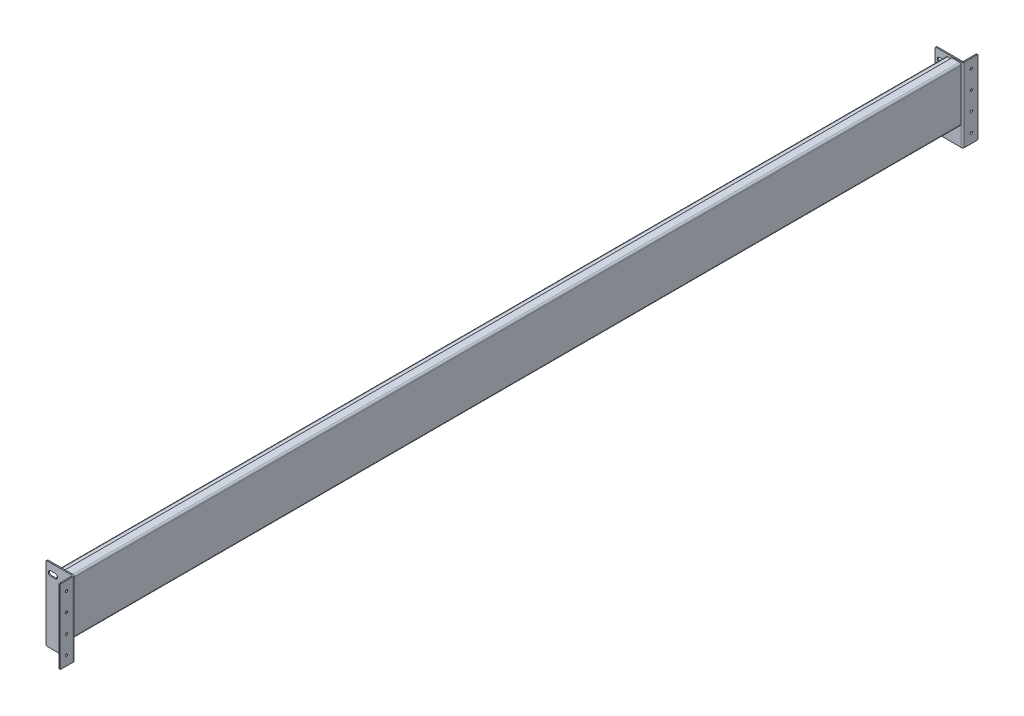
SolidWorks part; units mm, degrees
material "ASTM A36 Steel"
ref_plane "Front Plane" through (0, 0, 0) normal (0, 0, 1) x (1, 0, 0)
ref_plane "Top Plane" through (0, 0, 0) normal (0, 1, 0) x (1, 0, 0)
ref_plane "Right Plane" through (0, 0, 0) normal (1, 0, 0) x (0, 0, -1)
sketch "Sketch1" plane through (0, 0, 0) normal (0, 0, 1) x (1, 0, 0)
  line L0 (6.35, 71.4375) -> (26.9875, 71.4375)
  line L1 (-22.225, -74.6125) -> (26.9875, -74.6125)
  line L2 (28.575, -69.85) -> (28.575, 69.85)
  line L3 (6.35, 74.6125) -> (26.9875, 74.6125)
  line L4 (31.75, -69.85) -> (31.75, 69.85)
  line L5 (-31.75, -74.6125) -> (31.75, 74.6125) construction
  line L6 (-31.75, 74.6125) -> (31.75, -74.6125) construction
  line L7 (0, 0) -> (0, 50000) construction
  line L8 (0, 0) -> (50000, 0) construction
  line L9 (-22.225, -71.4375) -> (26.9875, -71.4375)
  line L10 (6.35, 74.6125) -> (6.35, 71.4375)
  line L11 (-22.225, -71.4375) -> (-22.225, -74.6125)
  arc A0 (26.9875, 74.6125) -> (31.75, 69.85) centre (26.9875, 69.85) cw
  arc A1 (31.75, -69.85) -> (26.9875, -74.6125) centre (26.9875, -69.85) cw
  arc A2 (26.9875, 71.4375) -> (28.575, 69.85) centre (26.9875, 69.85) cw
  arc A3 (28.575, -69.85) -> (26.9875, -71.4375) centre (26.9875, -69.85) cw
  point P0 (0, 0)
  dimension "D3" = 4.7625
  dimension "D1" = 149.225
  dimension "D2" = 63.5
  dimension "D4" = 74.6125
  dimension "D5" = 25.4
  dimension "D6" = 31.75
  dimension "D7" = 22.225
  dimension "D8" = 3.175
extrude "Boss-Extrude1" add sketch "Sketch1" along normal blind 1216.025 and the other way blind 1216.025
sketch "Sketch2" plane through (0, 0, 0) normal (0, 0, 1) x (1, 0, 0)
  line L0 (22.225, 71.4375) -> (-4.7625, 71.4375)
  line L1 (6.35, 71.4375) -> (26.9875, 71.4375) construction
  line L2 (-9.525, 66.675) -> (-9.525, 38.1)
  line L3 (-14.2875, 33.3375) -> (-26.9875, 33.3375)
  line L4 (-31.75, 28.575) -> (-31.75, -66.675)
  line L5 (-26.9875, -71.4375) -> (22.225, -71.4375)
  line L6 (26.9875, -71.4375) -> (-22.225, -71.4375) construction
  line L7 (31.75, -69.85) -> (31.75, 69.85) construction
  line L11 (26.9875, 74.6125) -> (6.35, 74.6125) construction
  line L12 (28.575, 69.85) -> (28.575, -69.85) construction
  line L13 (22.225, 68.2625) -> (-4.7625, 68.2625)
  line L14 (-6.35, 66.675) -> (-6.35, 38.1)
  line L15 (-14.2875, 30.1625) -> (-26.9875, 30.1625)
  line L16 (-28.575, 28.575) -> (-28.575, -66.675)
  line L17 (-26.9875, -68.2625) -> (22.225, -68.2625)
  line L18 (22.225, 68.2625) -> (22.225, 71.4375)
  line L19 (22.225, -68.2625) -> (22.225, -71.4375)
  arc A0 (-26.9875, -71.4375) -> (-31.75, -66.675) centre (-26.9875, -66.675) cw
  arc A1 (-4.7625, 71.4375) -> (-9.525, 66.675) centre (-4.7625, 66.675) ccw
  arc A2 (-9.525, 38.1) -> (-14.2875, 33.3375) centre (-14.2875, 38.1) cw
  arc A3 (-26.9875, 33.3375) -> (-31.75, 28.575) centre (-26.9875, 28.575) ccw
  arc A4 (-4.7625, 68.2625) -> (-6.35, 66.675) centre (-4.7625, 66.675) ccw
  arc A5 (-6.35, 38.1) -> (-14.2875, 30.1625) centre (-14.2875, 38.1) cw
  arc A6 (-26.9875, 30.1625) -> (-28.575, 28.575) centre (-26.9875, 28.575) ccw
  arc A7 (-26.9875, -68.2625) -> (-28.575, -66.675) centre (-26.9875, -66.675) cw
  point P21 (-31.75, -71.4375)
  point P28 (-31.75, 33.3375)
  dimension "D7" = 4.7625
  dimension "D1" = 63.5
  dimension "D2" = 22.225
  dimension "D3" = 41.275
  dimension "D4" = 104.775
  dimension "D5" = 6.35
  dimension "D6" = 6.35
  dimension "D8" = 3.175
extrude "Boss-Extrude2" add sketch "Sketch2" along normal up to surface and the other way up to surface separate body
sketch "Sketch4" plane through (0, -74.6125, 0) normal (0, -1, 0) x (1, 0, 0)
  line L0 (-22.225, 1216.025) -> (26.9875, 1216.025) construction
  line L1 (-39.6875, 1216.025) -> (31.75, 1216.025)
  line L2 (33.3375, 1220.7875) -> (33.3375, 1257.3)
  line L3 (-26.9875, 1216.025) -> (-31.75, 1216.025) construction
  line L4 (-26.9875, 1216.025) -> (-31.75, 1216.025) construction
  line L5 (-39.6875, 1219.2) -> (31.75, 1219.2)
  line L6 (33.3375, 1257.3) -> (36.5125, 1257.3)
  line L7 (-39.6875, 1219.2) -> (-39.6875, 1216.025)
  line L8 (36.5125, 1257.3) -> (36.5125, 1220.7875)
  line L10 (-39.6875, 1216.025) -> (39.0982, 1216.025) construction
  line L11 (36.5125, 1830.3646) -> (36.5125, 1866.9) construction
  line L12 (33.3375, 1828.0786) -> (33.3375, 1866.9) construction
  line L13 (-39.6875, 1219.2) -> (38.5604, 1219.2) construction
  arc A0 (36.5125, 1220.7875) -> (31.75, 1216.025) centre (31.75, 1220.7875) cw
  arc A1 (33.3375, 1220.7875) -> (31.75, 1219.2) centre (31.75, 1220.7875) cw
  arc A2 (36.5125, 1830.3646) -> (39.0982, 1216.025) centre (-67.5809, 1522.7512) cw construction
  arc A3 (33.3375, 1828.0786) -> (38.5604, 1219.2) centre (-67.5809, 1522.7512) cw construction
  point P9 (36.5125, 1825.625)
  point P19 (36.5125, 1825.625)
  dimension "D4" = 76.2
  dimension "D3" = 4.7625
  dimension "D1" = 41.275
  dimension "D2" = 7.9375
  dimension "D5" = 3.175
extrude "Boss-Extrude3" add sketch "Sketch4" along normal blind 50.8 and the other way blind 152.4 separate body
sketch "Sketch5" plane through (33.3375, 0, 0) normal (1, 0, 0) x (0, 0, -1)
  line L0 (-1239.045, 77.7875) -> (-1239.045, -49922.2125) construction
  line L1 (-1257.3, 77.7875) -> (-1257.3, -125.4125) construction
  line L2 (-1257.3, 77.7875) -> (-1220.7875, 77.7875) construction
  circle A0 centre (-1239.045, 52.3875) radius 3.175
  circle A1 centre (-1239.045, 1.5875) radius 3.175
  circle A2 centre (-1239.045, -49.2125) radius 3.175
  circle A3 centre (-1239.045, -100.0125) radius 3.175
  dimension "D6" = 6.35
  dimension "D1" = 18.255
  dimension "D2" = 50.8
  dimension "D3" = 50.8
  dimension "D4" = 50.8
  dimension "D5" = 25.4
extrude "Cut-Extrude1" cut sketch "Sketch5" along normal through all
sketch "Sketch9" plane through (0, 0, 1216.025) normal (0, 0, -1) x (-1, 0, 0)
  line L0 (14.2875, 52.3875) -> (26.9875, 52.3875) construction
  line L1 (14.2875, 58.7375) -> (26.9875, 58.7375)
  line L2 (14.2875, 46.0375) -> (26.9875, 46.0375)
  line L3 (39.6875, 77.7875) -> (-31.75, 77.7875) construction
  line L4 (39.6875, 77.7875) -> (39.6875, -125.4125) construction
  arc A0 (14.2875, 58.7375) -> (14.2875, 46.0375) centre (14.2875, 52.3875) ccw
  arc A1 (26.9875, 46.0375) -> (26.9875, 58.7375) centre (26.9875, 52.3875) ccw
  point P2 (20.6375, 52.3875)
  dimension "D1" = 25.4
  dimension "D2" = 12.7
  dimension "D3" = 12.7
  dimension "D4" = 19.05
extrude "Cut-Extrude2" cut sketch "Sketch9" against normal blind 3.175
sketch "Sketch10" plane through (0, -74.6125, 0) normal (0, -1, 0) x (1, 0, 0)
  line L0 (10.3187, 1196.975) -> (-5.5563, 1196.975) construction
  line L1 (10.3187, 1192.2125) -> (-5.5563, 1192.2125)
  line L2 (10.3187, 1201.7375) -> (-5.5563, 1201.7375)
  line L3 (-22.225, 1216.025) -> (26.9875, 1216.025) construction
  line L4 (2.3812, 1825.625) -> (2.3812, -48174.375) construction
  arc A0 (10.3187, 1192.2125) -> (10.3187, 1201.7375) centre (10.3187, 1196.975) ccw
  arc A1 (-5.5563, 1201.7375) -> (-5.5563, 1192.2125) centre (-5.5563, 1196.975) ccw
  point P2 (2.3812, 1196.975)
  point P11 (2.3812, 1216.025)
  dimension "D1" = 19.05
  dimension "D2" = 15.875
  dimension "D3" = 9.525
extrude "Cut-Extrude3" cut sketch "Sketch10" against normal blind 9.525
mirror "Mirror2" about plane through (0, 0, 0) normal (0, 0, 1) of "Cut-Extrude3"
fillet "Fillet1" radius 2.54 4 edges at (34.925, 77.7875, 1257.3) (34.925, -125.4125, 1257.3) (-39.6875, -125.4125, 1217.6125) (-39.6875, 77.7875, 1217.6125)
mirror "Mirror3" about plane through (0, 0, 0) normal (0, 0, 1) of bodies 119
